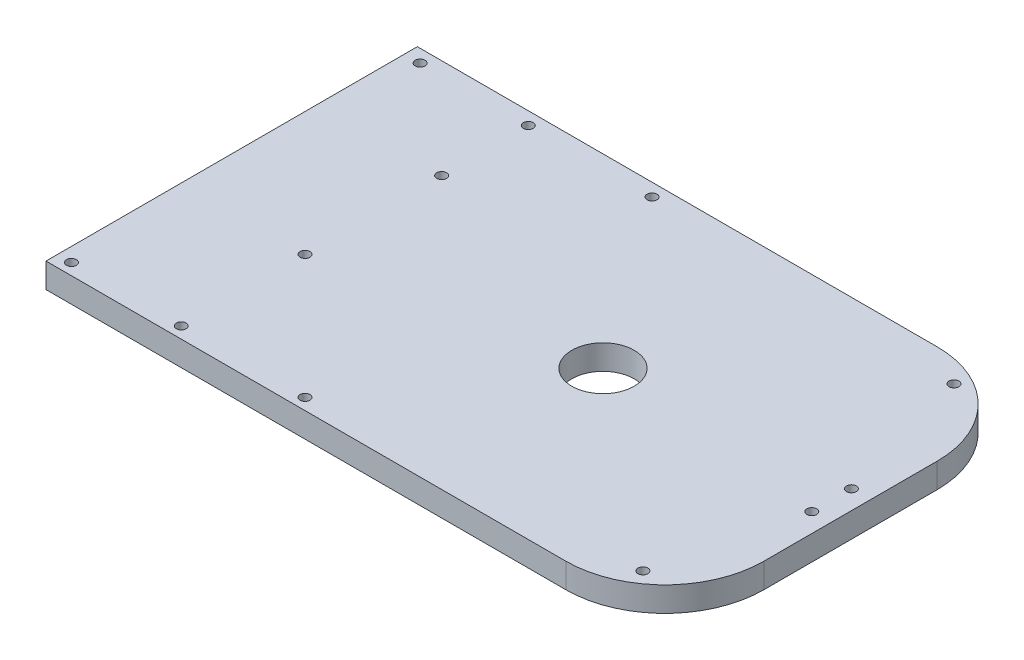
SolidWorks part; units mm, degrees
ref_plane "Front Plane" through (0, 0, 0) normal (0, 0, 1) x (1, 0, 0)
ref_plane "Top Plane" through (0, 0, 0) normal (0, 1, 0) x (1, 0, 0)
ref_plane "Right Plane" through (0, 0, 0) normal (1, 0, 0) x (0, 0, -1)
sketch "Sketch1" plane through (0, 0, 0) normal (0, 1, 0) x (1, 0, 0)
  line L1 (0, 0) -> (210, 0)
  line L2 (0, 0) -> (0, 150)
  line L3 (0, 150) -> (210, 150)
  line L4 (250, 40) -> (250, 110)
  arc A0 (250, 110) -> (210, 150) centre (210, 110) ccw
  arc A1 (210, 0) -> (250, 40) centre (210, 40) ccw
  point P7 (250, 150)
  dimension "D3" = 40
  dimension "D4" = 40
  dimension "D1" = 250
  dimension "D2" = 150
extrude "Boss-Extrude1" add sketch "Sketch1" along normal blind 10
sketch "Sketch2" plane through (0, 0, 0) normal (0, -1, 0) x (1, 0, 0)
  line L0 (0, 0) -> (210, 0) construction
  line L1 (250, -40) -> (250, -110) construction
  circle A0 centre (150, -75) radius 12.5979
  dimension "D1" = 25.1959
  dimension "D2" = 75
  dimension "D3" = 100
extrude "Cut-Extrude1" cut sketch "Sketch2" against normal through all
sketch "Sketch3" plane through (0, 10, 0) normal (0, 1, 0) x (1, 0, 0)
  line L0 (210, 150) -> (0, 150) construction
  line L1 (0, 150) -> (0, 0) construction
  circle A0 centre (6.3109, 144.8171) radius 2
  dimension "D1" = 4
  dimension "D2" = 5.1829
  dimension "D3" = 6.3109
sketch "Sketch4" plane through (0, 10, 0) normal (0, 1, 0) x (1, 0, 0)
  line L0 (0, 0) -> (210, 0) construction
  line L1 (0, 150) -> (0, 0) construction
  circle A0 centre (5.6357, 4.6328) radius 2
  dimension "D1" = 4
  dimension "D2" = 4.6328
  dimension "D3" = 5.6357
sketch "Sketch5" plane through (0, 10, 0) normal (0, 1, 0) x (1, 0, 0)
  circle A0 centre (226.3641, 140.4212) radius 2
  arc A1 (250, 110) -> (210, 150) centre (210, 110) ccw construction
  dimension "D1" = 4
  dimension "D2" = 34.5433
  dimension "D3" = 30.4212
sketch "Sketch6" plane through (0, 10, 0) normal (0, 1, 0) x (1, 0, 0)
  circle A0 centre (228.9499, 12.1646) radius 2
  arc A1 (210, 0) -> (250, 40) centre (210, 40) ccw construction
  dimension "D1" = 4
  dimension "D2" = 33.6736
  dimension "D3" = 18.9499
sketch "Sketch10" plane through (0, 10, 0) normal (0, 1, 0) x (1, 0, 0)
  line L0 (210, 150) -> (0, 150) construction
  line L1 (0, 150) -> (0, 0) construction
  line L2 (0, 0) -> (210, 0) construction
  circle A0 centre (50, 144.82) radius 2
  circle A1 centre (50, 4.63) radius 2
  circle A3 centre (100, 4.63) radius 2
  circle A4 centre (100, 144.82) radius 2
  circle A5 centre (50, 109.82) radius 2
  circle A6 centre (50, 54.63) radius 2
  dimension "D1" = 4
  dimension "D4" = 4
  dimension "D9" = 4
  dimension "D10" = 4
  dimension "D15" = 4
  dimension "D18" = 4
  dimension "D14" = 50
  dimension "D17" = 50
  dimension "D2" = 5.18
  dimension "D3" = 50
  dimension "D5" = 4.63
  dimension "D6" = 50
  dimension "D7" = 50
  dimension "D8" = 4.63
  dimension "D11" = 50
  dimension "D12" = 5.18
  dimension "D13" = 35
  dimension "D16" = 50
extrude "Cut-Extrude10" cut sketch "Sketch3" against normal through all
extrude "Cut-Extrude11" cut sketch "Sketch4" against normal through all
extrude "Cut-Extrude12" cut sketch "Sketch5" against normal through all
extrude "Cut-Extrude13" cut sketch "Sketch6" against normal through all
extrude "Cut-Extrude15" cut sketch "Sketch10" against normal through all
sketch "Sketch11" plane through (0, 10, 0) normal (0, 1, 0) x (1, 0, 0)
  line L0 (250, 40) -> (250, 110) construction
  line L1 (210, 150) -> (0, 150) construction
  line L2 (0, 0) -> (210, 0) construction
  circle A0 centre (242.34, 83) radius 2
  circle A1 centre (242.34, 67) radius 2
  dimension "D1" = 4
  dimension "D2" = 7.66
  dimension "D3" = 16
  dimension "D6" = 4
  dimension "D4" = 67
  dimension "D5" = 67
extrude "Cut-Extrude16" cut sketch "Sketch11" against normal through all
